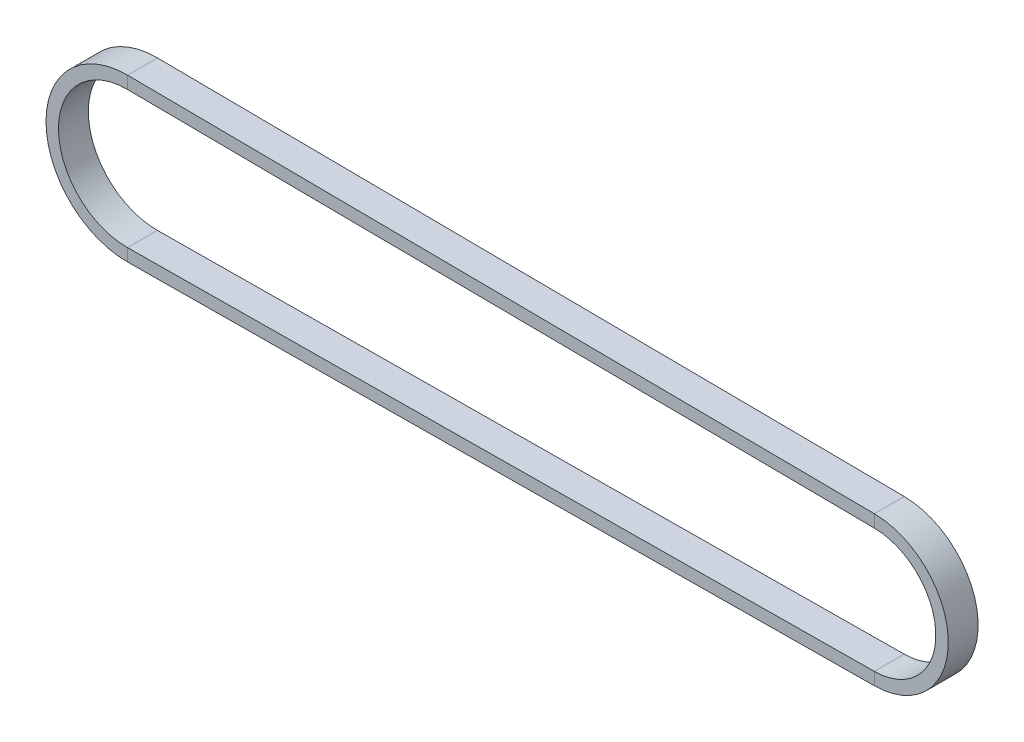
SolidWorks part; units mm, degrees
ref_plane "Front Plane" through (0, 0, 0) normal (0, 0, 1) x (1, 0, 0)
ref_plane "Top Plane" through (0, 0, 0) normal (0, 1, 0) x (1, 0, 0)
ref_plane "Right Plane" through (0, 0, 0) normal (1, 0, 0) x (0, 0, -1)
sketch "SK_Chain_Path" plane through (0, 0, 0) normal (0, 0, 1) x (1, 0, 0)
  line L0 (0, 0) -> (1, 0) construction
  line L1 (0, 0) -> (0, 1) construction
  line L2 (0.2354, -27.4245) -> (-299.7425, -29.9989)
  line L3 (-299.7425, 29.9989) -> (0.2354, 27.4245)
  arc A0 (0.2354, 27.4245) -> (0.2354, -27.4245) centre (0, 0) cw
  arc A1 (-299.7425, -29.9989) -> (-299.7425, 29.9989) centre (-300, 0) cw
ref_plane "PL_Chain_Profile" through (-299.7425, 29.9989, 0) normal (1, -0.0086, 0) x (0, 0, -1)
sketch "SK_Chain_Profile" plane through (-299.7425, 29.9989, 0) normal (1, -0.0086, 0) x (0, 0, -1)
  line L1 (6, -2.5) -> (-6, -2.5)
  line L2 (6, -2.5) -> (6, 2.5)
  line L3 (6, 2.5) -> (-6, 2.5)
  line L4 (-6, -2.5) -> (-6, 2.5)
  line L5 (6, -2.5) -> (-6, 2.5) construction
  line L6 (6, 2.5) -> (-6, -2.5) construction
  point P0 (0, 0)
  dimension "D1" = 5
  dimension "D2" = 12
sweep "FT_Chain_Envelope" add profiles "SK_Chain_Profile" path "SK_Chain_Path"
equation "\"WheelDiameter\"= 150mm"
equation "\"WheelRadius\"= \"WheelDiameter\" / 2"
equation "\"DT_WheelWidth\"= 45mm"
equation "\"DT_Wheelbase\"= 300mm"
equation "\"DT_ShaftDiameter\"= 12mm"
equation "\"DT_FrontShaftLength\"= 180mm"
equation "\"DT_RearShaftLength\"= 200mm"
equation "\"DT_BearingWidth\"= 20mm"
equation "\"DT_BearingHousingWidth\"= 60mm"
equation "\"DT_BearingHousingHeight\"= 35mm"
equation "\"DT_ChainPitch\"= 9.525mm"
equation "\"DT_SprocketTeeth\"= 18"
equation "\"DT_SprocketPitchDiameter\"= \"DT_ChainPitch\" / sin(180deg / \"DT_SprocketTeeth\")"
equation "\"DT_SprocketOuterDiameter\"= 60mm"
equation "\"DT_SprocketThickness\"= 6mm"
equation "\"DT_SprocketHubDiameter\"= 25mm"
equation "\"DT_SprocketHubLength\"= 20mm"
equation "\"DT_CouplingDiameter\"= 30mm"
equation "\"DT_CouplingLength\"= 35mm"
equation "\"DT_MotorDiameter\"= 60mm"
equation "\"DT_MotorLength\"= 120mm"
equation "\"DT_MotorShaftDiameter\"= 8mm"
equation "\"DT_MotorShaftLength\"= 20mm"
equation "\"Stripe_Width\"= \"WheelDiameter\" * 0.0533'\"Stripe"
equation "\"Stripe_Length\"= \"WheelDiameter\" * 0.2"
equation "\"Center_Offset\"= \"WheelDiameter\" / 3"
equation "\"DT_WheelBearingGap\" = 10mm"
equation "\"DT_BearingFaceGap\" = 50mm"
equation "\"DT_BearingCentreSpacing\" = \"DT_BearingFaceGap\" + \"DT_BearingWidth\""
equation "\"DT_SprocketBearingGap\"= (\"DT_BearingFaceGap\" - \"DT_SprocketHubLength\") / 2"
equation "\"DT_CouplingInternalGap\"= 5mm"
equation "\"DT_CouplingEngagement\"= (\"DT_CouplingLength\" - \"DT_CouplingInternalGap\") / 2"
equation "\"DT_MotorCouplingGap\"= \"DT_MotorShaftLength\" - \"DT_CouplingEngagement\""
equation "\"DT_ChainWidth\"= 12mm"
equation "\"DT_ChainThickness\"= 5mm"
